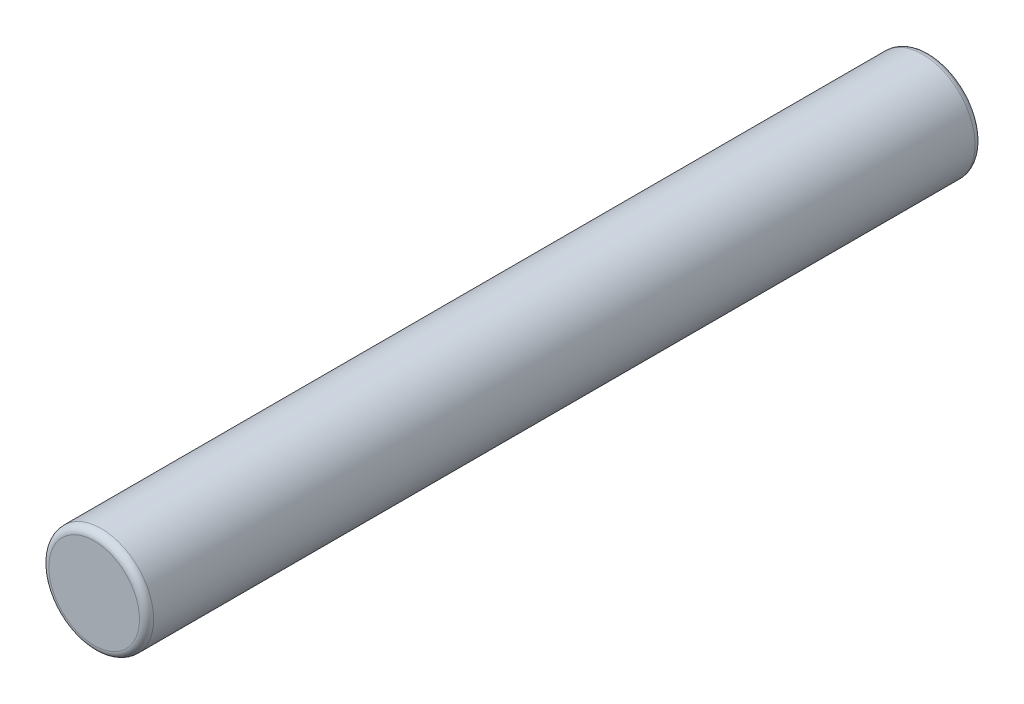
SolidWorks part; units mm, degrees
ref_plane "Alzado" through (0, 0, 0) normal (1, 0, 0) x (0, 1, 0)
ref_plane "Planta" through (0, 0, 0) normal (0, 0, 1) x (0, 1, 0)
ref_plane "Vista lateral" through (0, 0, 0) normal (0, 1, 0) x (-1, 0, 0)
sketch "Croquis2" plane through (0, 0, 0) normal (0, 0, 1) x (0, 1, 0)
  circle A0 centre (0, 0) radius 3.7
  dimension "D1" = 7.4
extrude "Saliente-Extruir1" add sketch "Croquis2" along normal blind 59
fillet "Redondeo1" radius 0.5 2 edges at (3.7, 0, 0) (3.7, 0, 59)
